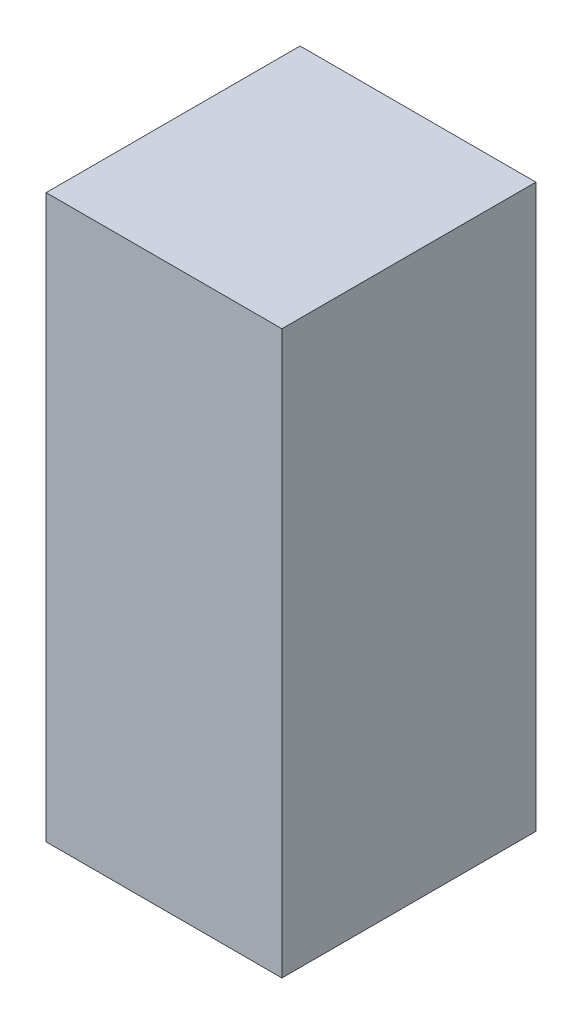
SolidWorks part; units mm, degrees
ref_plane "Front Plane" through (0, 0, 0) normal (0, 0, 1) x (1, 0, 0)
ref_plane "Top Plane" through (0, 0, 0) normal (0, 1, 0) x (1, 0, 0)
ref_plane "Right Plane" through (0, 0, 0) normal (1, 0, 0) x (0, 0, -1)
sketch "Sketch1" plane through (0, 0, 0) normal (0, 0, 1) x (1, 0, 0)
  line L1 (-130, 310) -> (0, 310)
  line L2 (-130, 310) -> (-130, 0)
  line L3 (-130, 0) -> (0, 0)
  line L4 (0, 310) -> (0, 0)
  point P4 (0, 0)
  point P5 (0, 0)
  point P7 (0, 0)
  point P8 (0, 0)
  dimension "D1" = 130
  dimension "D2" = 310
extrude "Boss-Extrude1" add sketch "Sketch1" along normal blind 140
